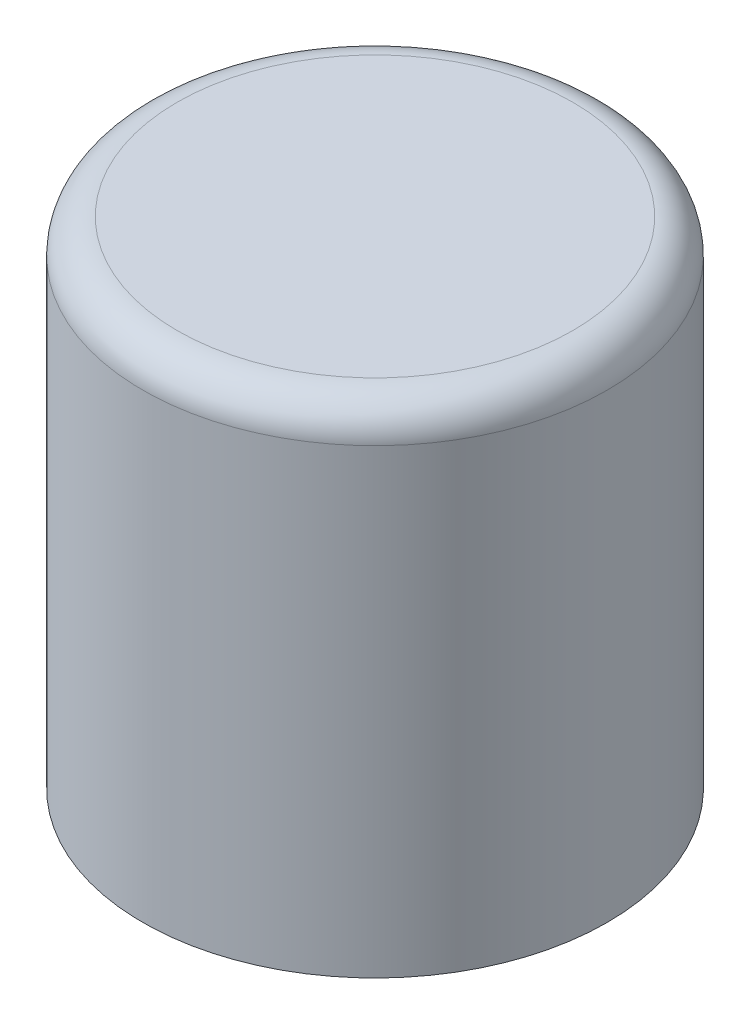
SolidWorks part; units mm, degrees
ref_plane "Plan de face" through (0, 0, 0) normal (0, 0, 1) x (1, 0, 0)
ref_plane "Plan de dessus" through (0, 0, 0) normal (0, 1, 0) x (1, 0, 0)
ref_plane "Plan de droite" through (0, 0, 0) normal (1, 0, 0) x (0, 0, -1)
sketch "Esquisse1" plane through (0, 0, 0) normal (0, 0, 1) x (1, 0, 0)
  line L0 (0, 0) -> (0, 28.8) construction
  line L2 (-13.5, 0) -> (-13.5, 28.8)
  line L3 (-13.5, 28.8) -> (0, 28.8)
  line L4 (0, 28.8) -> (0, 25.8)
  line L5 (0, 25.8) -> (-12.5, 25.8) construction
  line L6 (-12.5, 25.8) -> (-12.5, 2) construction
  line L7 (-12.5, 2) -> (-12, 2)
  line L8 (-12, 2) -> (-12, 0)
  line L17 (-12, 0) -> (-13.5, 0)
  line L18 (-12.5, 2) -> (-12.5, 3)
  line L19 (-12.5, 3) -> (-12, 3)
  line L20 (-12, 3) -> (-12, 25.8)
  line L21 (-12, 25.8) -> (0, 25.8)
  point P12 (-12, 0.038)
  dimension "D1" = 2
  dimension "D2" = 1
  dimension "D3" = 13.5
  dimension "D4" = 1
  dimension "D5" = 0.5
  dimension "D6" = 12
  dimension "D7" = 25.8
  dimension "D9" = 3
revolve "Révolution1" add sketch "Esquisse1" angle 360 about L0
fillet "Congé1" radius 2 1 edges at (13.5, 28.8, 0)
